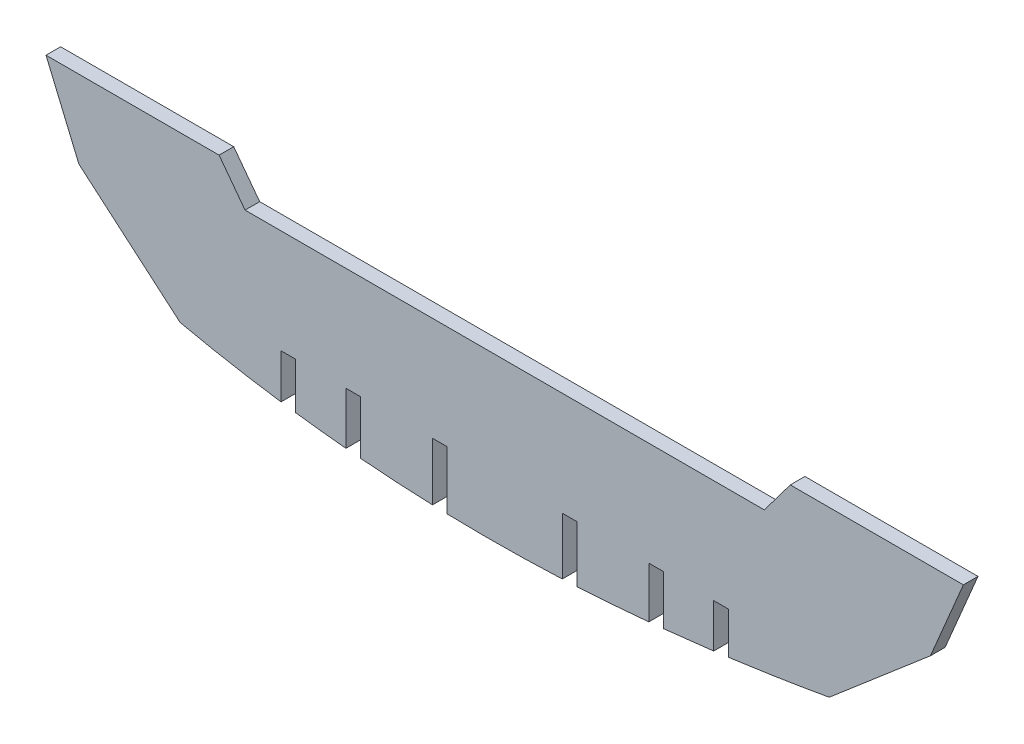
SolidWorks part; units mm, degrees
ref_plane "Front Plane" through (0, 0, 0) normal (0, 0, 1) x (1, 0, 0)
ref_plane "Top Plane" through (0, 0, 0) normal (0, 1, 0) x (1, 0, 0)
ref_plane "Right Plane" through (0, 0, 0) normal (1, 0, 0) x (0, 0, -1)
sketch "Sketch1" plane through (0, 0, 0) normal (0, 0, 1) x (1, 0, 0)
  line L0 (-76.2, 19.05) -> (-83.82, 29.21)
  line L1 (-83.82, 29.21) -> (-134.62, 29.21)
  line L2 (-76.2, -19.05) -> (-95.25, -19.05)
  line L3 (-76.2, 19.05) -> (76.2, 19.05)
  line L4 (-76.2, 19.05) -> (-76.2, -19.05)
  line L5 (-76.2, -19.05) -> (76.2, -19.05)
  line L6 (76.2, 19.05) -> (76.2, -19.05)
  line L7 (-76.2, 19.05) -> (76.2, -19.05) construction
  line L8 (-76.2, -19.05) -> (76.2, 19.05) construction
  line L9 (-95.25, -19.05) -> (-124.968, 6.35)
  line L10 (76.2, 19.05) -> (83.82, 29.21)
  line L11 (83.82, 29.21) -> (134.62, 29.21)
  line L12 (134.62, 29.21) -> (124.968, 6.35)
  line L13 (124.968, 6.35) -> (95.25, -19.05)
  line L14 (95.25, -19.05) -> (76.2, -19.05)
  spline S0 degree 1 poles (-134.62, 29.21) (-124.968, 6.35) knots 0 0 1 1
  spline S1 degree 3 poles (-95.25, -19.05) (-66.0792, -25.5147) (-2.1216, -32.0837) (61.7619, -25.0102) (95.25, -19.05) knots 0 0 0 0 0.467199 1 1 1 1
  point P4 (0, 0)
  dimension "D1" = 152.4
  dimension "D2" = 38.1
  dimension "D3" = 12.7
  dimension "D4" = 50.8
  dimension "D5" = 12.7
  dimension "D6" = 19.05
  dimension "D7" = 19.05
  dimension "D8" = 50.8
  dimension "D9" = 48.26
  dimension "D10" = 48.26
  dimension "D11" = 25.4
  dimension "D12" = 48.768
  dimension "D13" = 48.768
extrude "Boss-Extrude1" add sketch "Sketch1" along normal blind 4.2926 contours L1 S0 L9 L2 L4 L0 | L6 L3 L4 L5 | L2 S1 L14 L5 | L14 L13 L12 L11 L10 L6
sketch "Sketch3" plane through (0, 0, 4.2926) normal (0, 0, 1) x (1, 0, 0)
  line L1 (-65.6463, -31.75) -> (-61.3537, -31.75)
  line L2 (-65.6463, -31.75) -> (-65.6463, -11.43)
  line L3 (-65.6463, -11.43) -> (-61.3537, -11.43)
  line L4 (-61.3537, -31.75) -> (-61.3537, -11.43)
  line L5 (-65.6463, -31.75) -> (-61.3537, -11.43) construction
  line L6 (-65.6463, -11.43) -> (-61.3537, -31.75) construction
  line L7 (-46.5963, -31.75) -> (-42.3037, -31.75)
  line L8 (-46.5963, -31.75) -> (-46.5963, -11.43)
  line L9 (-46.5963, -11.43) -> (-42.3037, -11.43)
  line L10 (-42.3037, -31.75) -> (-42.3037, -11.43)
  line L11 (-46.5963, -31.75) -> (-42.3037, -11.43) construction
  line L12 (-46.5963, -11.43) -> (-42.3037, -31.75) construction
  line L13 (-21.1963, -11.43) -> (-16.9037, -11.43)
  line L14 (-21.1963, -11.43) -> (-21.1963, -31.75)
  line L15 (-21.1963, -31.75) -> (-16.9037, -31.75)
  line L16 (-16.9037, -11.43) -> (-16.9037, -31.75)
  line L17 (-21.1963, -11.43) -> (-16.9037, -31.75) construction
  line L18 (-21.1963, -31.75) -> (-16.9037, -11.43) construction
  line L19 (42.3037, -11.43) -> (46.5963, -11.43)
  line L20 (42.3037, -11.43) -> (42.3037, -31.75)
  line L21 (42.3037, -31.75) -> (46.5963, -31.75)
  line L22 (46.5963, -11.43) -> (46.5963, -31.75)
  line L23 (42.3037, -11.43) -> (46.5963, -31.75) construction
  line L24 (42.3037, -31.75) -> (46.5963, -11.43) construction
  line L25 (61.3537, -11.43) -> (65.6463, -11.43)
  line L26 (61.3537, -11.43) -> (61.3537, -31.75)
  line L27 (61.3537, -31.75) -> (65.6463, -31.75)
  line L28 (65.6463, -11.43) -> (65.6463, -31.75)
  line L29 (61.3537, -11.43) -> (65.6463, -31.75) construction
  line L30 (61.3537, -31.75) -> (65.6463, -11.43) construction
  line L34 (16.9037, -11.43) -> (21.1963, -11.43)
  line L35 (16.9037, -11.43) -> (16.9037, -31.75)
  line L36 (16.9037, -31.75) -> (21.1963, -31.75)
  line L37 (21.1963, -11.43) -> (21.1963, -31.75)
  line L38 (16.9037, -11.43) -> (21.1963, -31.75) construction
  line L39 (16.9037, -31.75) -> (21.1963, -11.43) construction
  line L43 (-83.82, 29.21) -> (-134.62, 29.21) construction
  point P0 (-63.5, -21.59)
  point P5 (-44.45, -21.59)
  point P10 (-19.05, -21.59)
  point P15 (44.45, -21.59)
  point P20 (63.5, -21.59)
  point P33 (19.05, -21.59)
  dimension "D1" = 4.2926
  dimension "D2" = 4.2926
  dimension "D3" = 4.2926
  dimension "D4" = 4.2926
  dimension "D5" = 4.2926
  dimension "D8" = 4.2926
  dimension "D10" = 19.05
  dimension "D11" = 19.05
  dimension "D12" = 19.05
  dimension "D13" = 19.05
  dimension "D14" = 31.75
  dimension "D9" = 40.64
  dimension "D6" = 12.7
  dimension "D7" = 12.7
extrude "Cut-Extrude2" cut sketch "Sketch3" against normal blind 4.2926
equation "\"thick\"=0.169"
equation "\"D1@Cut-Extrude1\"=\"thick\""
equation "\"D1@Sketch3\"=\"thick\""
equation "\"D2@Sketch3\"=\"thick\""
equation "\"D3@Sketch3\"=\"thick\""
equation "\"D4@Sketch3\"=\"thick\""
equation "\"D5@Sketch3\"=\"thick\""
equation "\"D8@Sketch3\"=\"thick\""
